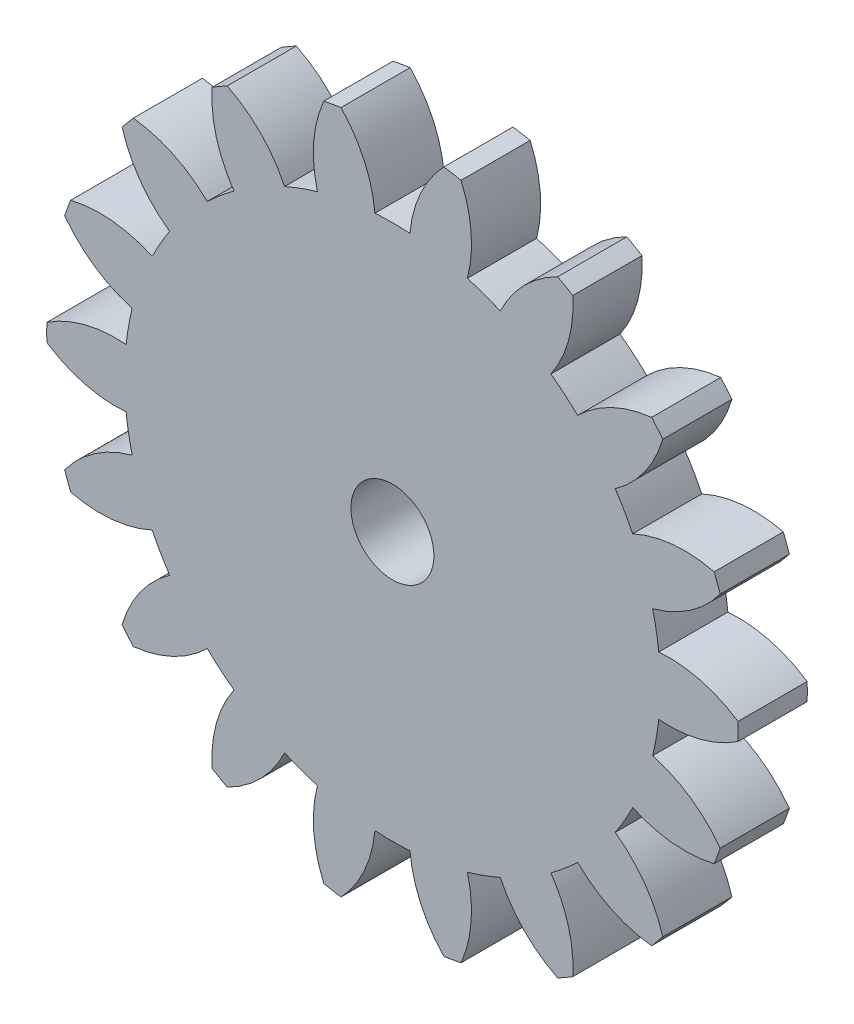
SolidWorks part; units mm, degrees
ref_plane "Front Plane" through (0, 0, 0) normal (0, 0, 1) x (1, 0, 0)
ref_plane "Top Plane" through (0, 0, 0) normal (0, 1, 0) x (1, 0, 0)
ref_plane "Right Plane" through (0, 0, 0) normal (1, 0, 0) x (0, 0, -1)
sketch "Sketch1" plane through (0, 0, 0) normal (0, 0, 1) x (1, 0, 0)
  circle A0 centre (0, 0) radius 3
  arc A72 (-19.5505, 15.5813) -> (-16.1103, 10.7616) centre (-10.9128, 18.1091) ccw
  arc A73 (-16.1103, 10.7616) -> (-17.3749, 8.5711) centre (0, 0) ccw
  arc A74 (-17.3749, 8.5711) -> (-23.2691, 9.1406) centre (-21.1394, 0.3962) ccw
  arc A75 (-23.2691, 9.1406) -> (-23.7006, 7.955) centre (0, 0) ccw
  arc A76 (-23.7006, 7.955) -> (-18.8194, 4.6025) centre (-16.4484, 13.2846) ccw
  arc A77 (-18.8194, 4.6025) -> (-19.2586, 2.1116) centre (0, 0) ccw
  arc A78 (-19.2586, 2.1116) -> (-24.992, 0.6309) centre (-20, -6.8578) ccw
  arc A79 (-24.992, 0.6309) -> (-24.992, -0.6309) centre (0, 0) ccw
  arc A80 (-24.992, -0.6309) -> (-19.2586, -2.1116) centre (-20, 6.8578) ccw
  arc A81 (-19.2586, -2.1116) -> (-18.8194, -4.6025) centre (0, 0) ccw
  arc A82 (-18.8194, -4.6025) -> (-23.7006, -7.955) centre (-16.4484, -13.2846) ccw
  arc A83 (-23.7006, -7.955) -> (-23.2691, -9.1406) centre (0, 0) ccw
  arc A84 (-23.2691, -9.1406) -> (-17.3749, -8.5711) centre (-21.1394, -0.3962) ccw
  arc A85 (-17.3749, -8.5711) -> (-16.1103, -10.7616) centre (0, 0) ccw
  arc A86 (-16.1103, -10.7616) -> (-19.5505, -15.5813) centre (-10.9128, -18.1091) ccw
  arc A87 (-19.5505, -15.5813) -> (-18.7395, -16.5478) centre (0, 0) ccw
  arc A88 (-18.7395, -16.5478) -> (-13.3956, -13.9968) centre (-19.729, -7.6024) ccw
  arc A89 (-13.3956, -13.9968) -> (-11.458, -15.6226) centre (0, 0) ccw
  arc A90 (-11.458, -15.6226) -> (-13.0424, -21.3283) centre (-4.061, -20.7494) ccw
  arc A91 (-13.0424, -21.3283) -> (-11.9497, -21.9592) centre (0, 0) ccw
  arc A92 (-11.9497, -21.9592) -> (-7.8006, -17.7342) centre (-15.939, -13.8916) ccw
  arc A93 (-7.8006, -17.7342) -> (-5.4238, -18.5993) centre (0, 0) ccw
  arc A94 (-5.4238, -18.5993) -> (-4.9611, -24.5028) centre (3.2806, -20.887) ccw
  arc A95 (-4.9611, -24.5028) -> (-3.7185, -24.7219) centre (0, 0) ccw
  arc A96 (-3.7185, -24.7219) -> (-1.2647, -19.3327) centre (-10.2266, -18.5053) ccw
  arc A97 (-1.2647, -19.3327) -> (1.2647, -19.3327) centre (0, 0) ccw
  arc A98 (1.2647, -19.3327) -> (3.7185, -24.7219) centre (10.2266, -18.5053) ccw
  arc A99 (3.7185, -24.7219) -> (4.9611, -24.5028) centre (0, 0) ccw
  arc A100 (4.9611, -24.5028) -> (5.4238, -18.5993) centre (-3.2806, -20.887) ccw
  arc A101 (5.4238, -18.5993) -> (7.8006, -17.7342) centre (0, 0) ccw
  arc A102 (7.8006, -17.7342) -> (11.9497, -21.9592) centre (15.939, -13.8916) ccw
  arc A103 (11.9497, -21.9592) -> (13.0424, -21.3283) centre (0, 0) ccw
  arc A104 (13.0424, -21.3283) -> (11.458, -15.6226) centre (4.061, -20.7494) ccw
  arc A105 (11.458, -15.6226) -> (13.3956, -13.9968) centre (0, 0) ccw
  arc A106 (13.3956, -13.9968) -> (18.7395, -16.5478) centre (19.729, -7.6024) ccw
  arc A107 (18.7395, -16.5478) -> (19.5505, -15.5813) centre (0, 0) ccw
  arc A108 (19.5505, -15.5813) -> (16.1103, -10.7616) centre (10.9128, -18.1091) ccw
  arc A109 (16.1103, -10.7616) -> (17.3749, -8.5711) centre (0, 0) ccw
  arc A110 (17.3749, -8.5711) -> (23.2691, -9.1406) centre (21.1394, -0.3962) ccw
  arc A111 (23.2691, -9.1406) -> (23.7006, -7.955) centre (0, 0) ccw
  arc A112 (23.7006, -7.955) -> (18.8194, -4.6025) centre (16.4484, -13.2846) ccw
  arc A113 (18.8194, -4.6025) -> (19.2586, -2.1116) centre (0, 0) ccw
  arc A114 (19.2586, -2.1116) -> (24.992, -0.6309) centre (20, 6.8578) ccw
  arc A115 (24.992, -0.6309) -> (24.992, 0.6309) centre (0, 0) ccw
  arc A116 (24.992, 0.6309) -> (19.2586, 2.1116) centre (20, -6.8578) ccw
  arc A117 (19.2586, 2.1116) -> (18.8194, 4.6025) centre (0, 0) ccw
  arc A118 (18.8194, 4.6025) -> (23.7006, 7.955) centre (16.4484, 13.2846) ccw
  arc A119 (23.7006, 7.955) -> (23.2691, 9.1406) centre (0, 0) ccw
  arc A120 (23.2691, 9.1406) -> (17.3749, 8.5711) centre (21.1394, 0.3962) ccw
  arc A121 (17.3749, 8.5711) -> (16.1103, 10.7616) centre (0, 0) ccw
  arc A122 (16.1103, 10.7616) -> (19.5505, 15.5813) centre (10.9128, 18.1091) ccw
  arc A123 (19.5505, 15.5813) -> (18.7395, 16.5478) centre (0, 0) ccw
  arc A124 (18.7395, 16.5478) -> (13.3956, 13.9968) centre (19.729, 7.6024) ccw
  arc A125 (13.3956, 13.9968) -> (11.458, 15.6226) centre (0, 0) ccw
  arc A126 (11.458, 15.6226) -> (13.0424, 21.3283) centre (4.061, 20.7494) ccw
  arc A127 (13.0424, 21.3283) -> (11.9497, 21.9592) centre (0, 0) ccw
  arc A128 (11.9497, 21.9592) -> (7.8006, 17.7342) centre (15.939, 13.8916) ccw
  arc A129 (7.8006, 17.7342) -> (5.4238, 18.5993) centre (0, 0) ccw
  arc A130 (5.4238, 18.5993) -> (4.9611, 24.5028) centre (-3.2806, 20.887) ccw
  arc A131 (4.9611, 24.5028) -> (3.7185, 24.7219) centre (0, 0) ccw
  arc A132 (3.7185, 24.7219) -> (1.2647, 19.3327) centre (10.2266, 18.5053) ccw
  arc A133 (1.2647, 19.3327) -> (-1.2647, 19.3327) centre (0, 0) ccw
  arc A134 (-1.2647, 19.3327) -> (-3.7185, 24.7219) centre (-10.2266, 18.5053) ccw
  arc A135 (-3.7185, 24.7219) -> (-4.9611, 24.5028) centre (0, 0) ccw
  arc A136 (-4.9611, 24.5028) -> (-5.4238, 18.5993) centre (3.2806, 20.887) ccw
  arc A137 (-5.4238, 18.5993) -> (-7.8006, 17.7342) centre (0, 0) ccw
  arc A138 (-7.8006, 17.7342) -> (-11.9497, 21.9592) centre (-15.939, 13.8916) ccw
  arc A139 (-11.9497, 21.9592) -> (-13.0424, 21.3283) centre (0, 0) ccw
  arc A140 (-13.0424, 21.3283) -> (-11.458, 15.6226) centre (-4.061, 20.7494) ccw
  arc A141 (-11.458, 15.6226) -> (-13.3956, 13.9968) centre (0, 0) ccw
  arc A142 (-13.3956, 13.9968) -> (-18.7395, 16.5478) centre (-19.729, 7.6024) ccw
  arc A143 (-18.7395, 16.5478) -> (-19.5505, 15.5813) centre (0, 0) ccw
  arc A144 (-19.5505, 15.5813) -> (-16.1103, 10.7616) centre (-10.9128, 18.1091) ccw
  arc A145 (-16.1103, 10.7616) -> (-17.3749, 8.5711) centre (0, 0) ccw
  arc A146 (-17.3749, 8.5711) -> (-23.2691, 9.1406) centre (-21.1394, 0.3962) ccw
  arc A147 (-23.2691, 9.1406) -> (-23.7006, 7.955) centre (0, 0) ccw
  arc A148 (-23.7006, 7.955) -> (-18.8194, 4.6025) centre (-16.4484, 13.2846) ccw
  arc A149 (-18.8194, 4.6025) -> (-19.2586, 2.1116) centre (0, 0) ccw
  arc A150 (-19.2586, 2.1116) -> (-24.992, 0.6309) centre (-20, -6.8578) ccw
  arc A151 (-24.992, 0.6309) -> (-24.992, -0.6309) centre (0, 0) ccw
  arc A152 (-24.992, -0.6309) -> (-19.2586, -2.1116) centre (-20, 6.8578) ccw
  arc A153 (-19.2586, -2.1116) -> (-18.8194, -4.6025) centre (0, 0) ccw
  arc A154 (-18.8194, -4.6025) -> (-23.7006, -7.955) centre (-16.4484, -13.2846) ccw
  arc A155 (-23.7006, -7.955) -> (-23.2691, -9.1406) centre (0, 0) ccw
  arc A156 (-23.2691, -9.1406) -> (-17.3749, -8.5711) centre (-21.1394, -0.3962) ccw
  arc A157 (-17.3749, -8.5711) -> (-16.1103, -10.7616) centre (0, 0) ccw
  arc A158 (-16.1103, -10.7616) -> (-19.5505, -15.5813) centre (-10.9128, -18.1091) ccw
  arc A159 (-19.5505, -15.5813) -> (-18.7395, -16.5478) centre (0, 0) ccw
  arc A160 (-18.7395, -16.5478) -> (-13.3956, -13.9968) centre (-19.729, -7.6024) ccw
  arc A161 (-13.3956, -13.9968) -> (-11.458, -15.6226) centre (0, 0) ccw
  arc A162 (-11.458, -15.6226) -> (-13.0424, -21.3283) centre (-4.061, -20.7494) ccw
  arc A163 (-13.0424, -21.3283) -> (-11.9497, -21.9592) centre (0, 0) ccw
  arc A164 (-11.9497, -21.9592) -> (-7.8006, -17.7342) centre (-15.939, -13.8916) ccw
  arc A165 (-7.8006, -17.7342) -> (-5.4238, -18.5993) centre (0, 0) ccw
  arc A166 (-5.4238, -18.5993) -> (-4.9611, -24.5028) centre (3.2806, -20.887) ccw
  arc A167 (-4.9611, -24.5028) -> (-3.7185, -24.7219) centre (0, 0) ccw
  arc A168 (-3.7185, -24.7219) -> (-1.2647, -19.3327) centre (-10.2266, -18.5053) ccw
  arc A169 (-1.2647, -19.3327) -> (1.2647, -19.3327) centre (0, 0) ccw
  arc A170 (1.2647, -19.3327) -> (3.7185, -24.7219) centre (10.2266, -18.5053) ccw
  arc A171 (3.7185, -24.7219) -> (4.9611, -24.5028) centre (0, 0) ccw
  arc A172 (4.9611, -24.5028) -> (5.4238, -18.5993) centre (-3.2806, -20.887) ccw
  arc A173 (5.4238, -18.5993) -> (7.8006, -17.7342) centre (0, 0) ccw
  arc A174 (7.8006, -17.7342) -> (11.9497, -21.9592) centre (15.939, -13.8916) ccw
  arc A175 (11.9497, -21.9592) -> (13.0424, -21.3283) centre (0, 0) ccw
  arc A176 (13.0424, -21.3283) -> (11.458, -15.6226) centre (4.061, -20.7494) ccw
  arc A177 (11.458, -15.6226) -> (13.3956, -13.9968) centre (0, 0) ccw
  arc A178 (13.3956, -13.9968) -> (18.7395, -16.5478) centre (19.729, -7.6024) ccw
  arc A179 (18.7395, -16.5478) -> (19.5505, -15.5813) centre (0, 0) ccw
  arc A180 (19.5505, -15.5813) -> (16.1103, -10.7616) centre (10.9128, -18.1091) ccw
  arc A181 (16.1103, -10.7616) -> (17.3749, -8.5711) centre (0, 0) ccw
  arc A182 (17.3749, -8.5711) -> (23.2691, -9.1406) centre (21.1394, -0.3962) ccw
  arc A183 (23.2691, -9.1406) -> (23.7006, -7.955) centre (0, 0) ccw
  arc A184 (23.7006, -7.955) -> (18.8194, -4.6025) centre (16.4484, -13.2846) ccw
  arc A185 (18.8194, -4.6025) -> (19.2586, -2.1116) centre (0, 0) ccw
  arc A186 (19.2586, -2.1116) -> (24.992, -0.6309) centre (20, 6.8578) ccw
  arc A187 (24.992, -0.6309) -> (24.992, 0.6309) centre (0, 0) ccw
  arc A188 (24.992, 0.6309) -> (19.2586, 2.1116) centre (20, -6.8578) ccw
  arc A189 (19.2586, 2.1116) -> (18.8194, 4.6025) centre (0, 0) ccw
  arc A190 (18.8194, 4.6025) -> (23.7006, 7.955) centre (16.4484, 13.2846) ccw
  arc A191 (23.7006, 7.955) -> (23.2691, 9.1406) centre (0, 0) ccw
  arc A192 (23.2691, 9.1406) -> (17.3749, 8.5711) centre (21.1394, 0.3962) ccw
  arc A193 (17.3749, 8.5711) -> (16.1103, 10.7616) centre (0, 0) ccw
  arc A194 (16.1103, 10.7616) -> (19.5505, 15.5813) centre (10.9128, 18.1091) ccw
  arc A195 (19.5505, 15.5813) -> (18.7395, 16.5478) centre (0, 0) ccw
  arc A196 (18.7395, 16.5478) -> (13.3956, 13.9968) centre (19.729, 7.6024) ccw
  arc A197 (13.3956, 13.9968) -> (11.458, 15.6226) centre (0, 0) ccw
  arc A198 (11.458, 15.6226) -> (13.0424, 21.3283) centre (4.061, 20.7494) ccw
  arc A199 (13.0424, 21.3283) -> (11.9497, 21.9592) centre (0, 0) ccw
  arc A200 (11.9497, 21.9592) -> (7.8006, 17.7342) centre (15.939, 13.8916) ccw
  arc A201 (7.8006, 17.7342) -> (5.4238, 18.5993) centre (0, 0) ccw
  arc A202 (5.4238, 18.5993) -> (4.9611, 24.5028) centre (-3.2806, 20.887) ccw
  arc A203 (4.9611, 24.5028) -> (3.7185, 24.7219) centre (0, 0) ccw
  arc A204 (3.7185, 24.7219) -> (1.2647, 19.3327) centre (10.2266, 18.5053) ccw
  arc A205 (1.2647, 19.3327) -> (-1.2647, 19.3327) centre (0, 0) ccw
  arc A206 (-1.2647, 19.3327) -> (-3.7185, 24.7219) centre (-10.2266, 18.5053) ccw
  arc A207 (-3.7185, 24.7219) -> (-4.9611, 24.5028) centre (0, 0) ccw
  arc A208 (-4.9611, 24.5028) -> (-5.4238, 18.5993) centre (3.2806, 20.887) ccw
  arc A209 (-5.4238, 18.5993) -> (-7.8006, 17.7342) centre (0, 0) ccw
  arc A210 (-7.8006, 17.7342) -> (-11.9497, 21.9592) centre (-15.939, 13.8916) ccw
  arc A211 (-11.9497, 21.9592) -> (-13.0424, 21.3283) centre (0, 0) ccw
  arc A212 (-13.0424, 21.3283) -> (-11.458, 15.6226) centre (-4.061, 20.7494) ccw
  arc A213 (-11.458, 15.6226) -> (-13.3956, 13.9968) centre (0, 0) ccw
  arc A214 (-13.3956, 13.9968) -> (-18.7395, 16.5478) centre (-19.729, 7.6024) ccw
  arc A215 (-18.7395, 16.5478) -> (-19.5505, 15.5813) centre (0, 0) ccw
  dimension "D1" = 0
extrude "Boss-Extrude2" add sketch "Sketch1" along normal blind 5
